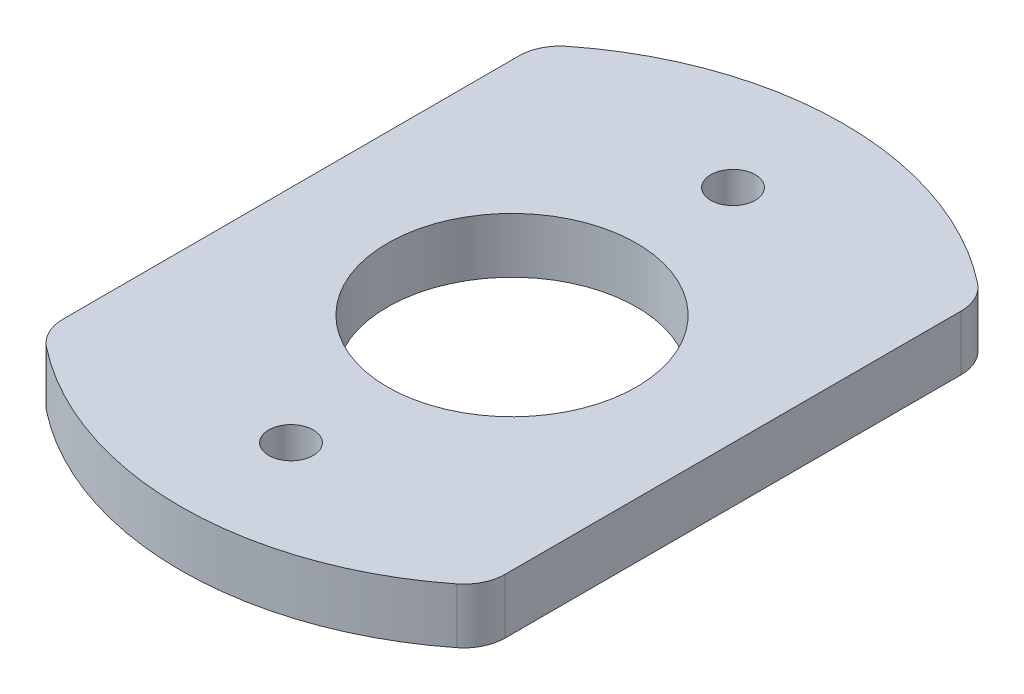
SolidWorks part; units mm, degrees
material "6061 Alloy"
ref_plane "Front" through (0, 0, 0) normal (0, 0, 1) x (1, 0, 0)
ref_plane "Top" through (0, 0, 0) normal (0, 1, 0) x (1, 0, 0)
ref_plane "Right" through (0, 0, 0) normal (1, 0, 0) x (0, 0, -1)
sketch "Sketch1" plane through (0, 0, 0) normal (0, 1, 0) x (1, 0, 0)
  circle A0 centre (0, 0) radius 38.1
  circle A1 centre (0, 0) radius 14.3129
  circle A2 centre (0, 0) radius 25.4 construction
  circle A3 centre (0, 25.4) radius 3.175 construction
  circle A4 centre (25.4, 0) radius 3.175 construction
  circle A5 centre (0, -25.4) radius 3.175 construction
  circle A6 centre (-25.4, 0) radius 3.175 construction
  dimension "D1" = 6.35
  dimension "D2" = 28.6258
  dimension "D3" = 9.525
  dimension "D4" = 50.8
extrude "Boss-Extrude1" add sketch "Sketch1" along normal blind 6.35
hole_wizard "#10 Clearance Hole1" positions "Sketch2" profile "Sketch3" hole size "#10" standard "ANSI Inch"
sketch "Sketch2" plane through (0, 6.35, 0) normal (0, 1, 0) x (1, 0, 0)
  point P0 (-25.4, 0)
  point P3 (0, 25.4)
  point P6 (25.4, 0)
  point P9 (0, -25.4)
sketch "Sketch3" plane through (-25.4, 6.35, 0) normal (1, 0, 0) x (0, 0, 1)
  line L0 (0, 0) -> (0, 6.35)
  line L1 (0, 6.35) -> (2.5527, 6.35)
  line L2 (2.5527, 6.35) -> (2.5527, 0)
  line L5 (2.5527, 0) -> (0, 0)
  line L11 (0, -6.35) -> (0, 107.95) construction
  dimension "Thru Hole Dia." = 5.1054
  dimension "Thru Hole Depth" = 6.35
sketch "Sketch4" plane through (0, 6.35, 0) normal (0, 1, 0) x (1, 0, 0)
  line L0 (-25.4, -26.1817) -> (-25.4, 26.1817)
  line L1 (25.4, -26.1817) -> (25.4, 26.1817)
  arc A0 (23.5857, 29.922) -> (-23.5857, 29.922) centre (0, 0) ccw
  circle A1 centre (0, 0) radius 38.1
  arc A2 (-23.5857, -29.922) -> (23.5857, -29.922) centre (0, 0) ccw
  arc A3 (-23.5857, -29.922) -> (-25.4, -26.1817) centre (-20.6375, -26.1817) cw
  arc A4 (25.4, -26.1817) -> (23.5857, -29.922) centre (20.6375, -26.1817) cw
  arc A5 (25.4, 26.1817) -> (23.5857, 29.922) centre (20.6375, 26.1817) ccw
  arc A6 (-23.5857, 29.922) -> (-25.4, 26.1817) centre (-20.6375, 26.1817) ccw
  point P13 (25.4, 28.3981)
  dimension "D3" = 4.7625
  dimension "D1" = 0
  dimension "D2" = 50.8
extrude "Cut-Extrude1" cut sketch "Sketch4" against normal through all flip side to cut
hole_wizard "#10 Clearance Hole2" positions "Sketch5" profile "Sketch6" hole size "#10" standard "ANSI Inch" end condition through all
sketch "Sketch5" plane through (0, 6.35, 0) normal (0, 1, 0) x (1, 0, 0)
  point P0 (0, 25.4)
  point P3 (0, -25.4)
sketch "Sketch6" plane through (0, 6.35, -25.4) normal (1, 0, 0) x (0, 0, 1)
  line L0 (0, 0) -> (0, 6.35)
  line L1 (0, 6.35) -> (2.5527, 6.35)
  line L2 (2.5527, 6.35) -> (2.5527, 0)
  line L5 (2.5527, 0) -> (0, 0)
  line L11 (0, -6.35) -> (0, 107.95) construction
  dimension "Thru Hole Dia." = 5.1054
  dimension "Thru Hole Depth" = 6.35
